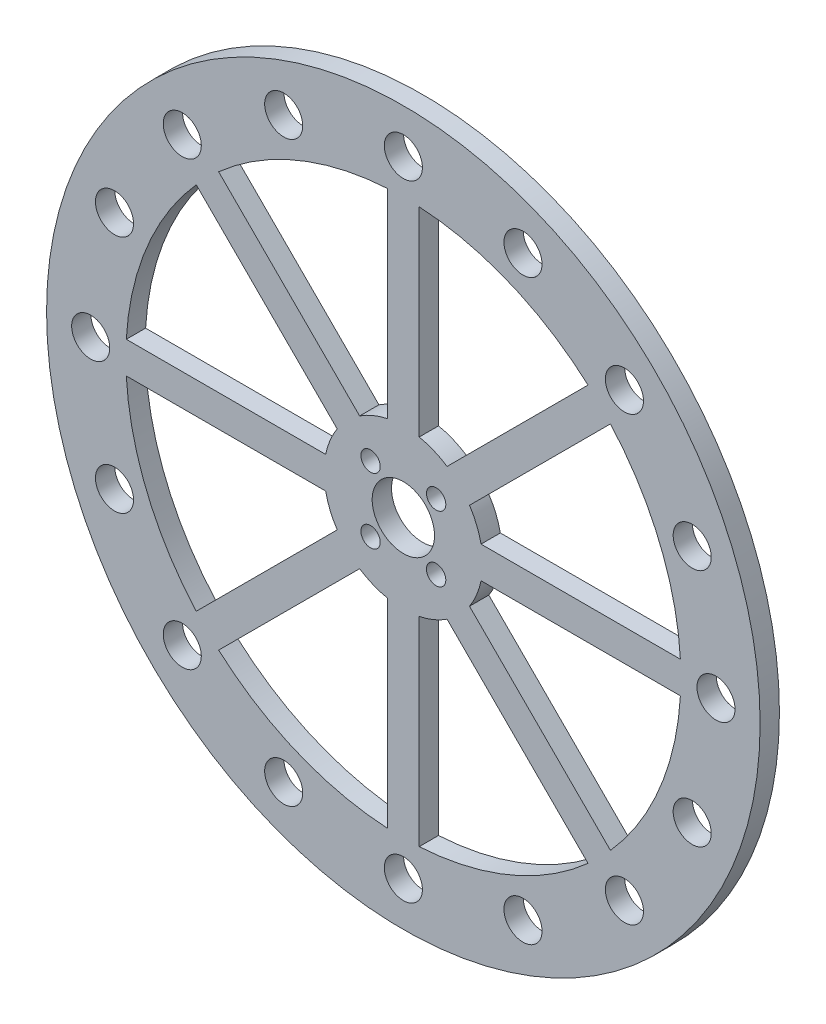
SolidWorks part; units mm, degrees
ref_plane "Front Plane" through (0, 0, 0) normal (0, 0, 1) x (1, 0, 0)
ref_plane "Top Plane" through (0, 0, 0) normal (0, 1, 0) x (1, 0, 0)
ref_plane "Right Plane" through (0, 0, 0) normal (1, 0, 0) x (0, 0, -1)
sketch "Model" plane through (0, 0, 0) normal (0, 0, 1) x (1, 0, 0)
  line L0 (-34.0565, 30.369) -> (-10.8762, 7.1887)
  line L1 (-12.7738, 2.6074) -> (-45.5557, 2.6074)
  line L2 (-7.1887, 10.8762) -> (-30.369, 34.0565)
  line L3 (-2.6074, 45.5557) -> (-2.6074, 12.7738)
  line L4 (2.6074, 12.7738) -> (2.6074, 45.5557)
  line L5 (30.369, 34.0565) -> (7.1887, 10.8762)
  line L6 (10.8762, 7.1887) -> (34.0565, 30.369)
  line L7 (45.5557, 2.6074) -> (12.7738, 2.6074)
  line L8 (12.7738, -2.6074) -> (45.5557, -2.6074)
  line L9 (34.0565, -30.369) -> (10.8762, -7.1887)
  line L10 (7.1887, -10.8762) -> (30.369, -34.0565)
  line L11 (2.6074, -45.5557) -> (2.6074, -12.7738)
  line L12 (-45.5557, -2.6074) -> (-12.7738, -2.6074)
  line L13 (-10.8762, -7.1887) -> (-34.0565, -30.369)
  line L14 (-2.6074, -12.7738) -> (-2.6074, -45.5557)
  line L15 (-30.369, -34.0565) -> (-7.1887, -10.8762)
  circle A0 centre (5.3894, 5.3586) radius 1.5912
  circle A1 centre (0, 0) radius 5.125
  circle A2 centre (-5.3894, 5.3586) radius 1.5912
  circle A3 centre (-5.3894, -5.4202) radius 1.5912
  circle A4 centre (5.3894, -5.4202) radius 1.5912
  circle A5 centre (-51.4095, 0) radius 3.131
  circle A6 centre (-47.4962, 19.6736) radius 3.131
  circle A7 centre (-36.352, 36.352) radius 3.131
  circle A8 centre (-19.6736, 47.4962) radius 3.131
  circle A9 centre (0, 51.4095) radius 3.131
  circle A10 centre (19.6736, 47.4962) radius 3.131
  circle A11 centre (36.352, 36.352) radius 3.131
  circle A12 centre (47.4962, 19.6736) radius 3.131
  circle A13 centre (51.4095, 0) radius 3.131
  circle A14 centre (47.4962, -19.6736) radius 3.131
  circle A15 centre (36.352, -36.352) radius 3.131
  circle A16 centre (19.6736, -47.4962) radius 3.131
  circle A17 centre (0, -51.4095) radius 3.131
  circle A18 centre (-19.6736, -47.4962) radius 3.131
  circle A19 centre (-36.352, -36.352) radius 3.131
  circle A20 centre (-47.4962, -19.6736) radius 3.131
  circle A21 centre (0, 0) radius 58.6675
  arc A22 (-34.0565, 30.369) -> (-45.5557, 2.6074) centre (0, 0) ccw
  arc A23 (-10.8762, 7.1887) -> (-12.7738, 2.6074) centre (0, 0) ccw
  arc A24 (-2.6074, 12.7738) -> (-7.1887, 10.8762) centre (0, 0) ccw
  arc A25 (-2.6074, 45.5557) -> (-30.369, 34.0565) centre (0, 0) ccw
  arc A26 (7.1887, 10.8762) -> (2.6074, 12.7738) centre (0, 0) ccw
  arc A27 (30.369, 34.0565) -> (2.6074, 45.5557) centre (0, 0) ccw
  arc A28 (12.7738, 2.6074) -> (10.8762, 7.1887) centre (0, 0) ccw
  arc A29 (45.5557, 2.6074) -> (34.0565, 30.369) centre (0, 0) ccw
  arc A30 (10.8762, -7.1887) -> (12.7738, -2.6074) centre (0, 0) ccw
  arc A31 (34.0565, -30.369) -> (45.5557, -2.6074) centre (0, 0) ccw
  arc A32 (2.6074, -12.7738) -> (7.1887, -10.8762) centre (0, 0) ccw
  arc A33 (2.6074, -45.5557) -> (30.369, -34.0565) centre (0, 0) ccw
  arc A34 (-45.5557, -2.6074) -> (-34.0565, -30.369) centre (0, 0) ccw
  arc A35 (-12.7738, -2.6074) -> (-10.8762, -7.1887) centre (0, 0) ccw
  arc A36 (-7.1887, -10.8762) -> (-2.6074, -12.7738) centre (0, 0) ccw
  arc A37 (-30.369, -34.0565) -> (-2.6074, -45.5557) centre (0, 0) ccw
  dimension "D4" = 10.25
  dimension "D1" = 7.6
  dimension "D2" = 7.6
  dimension "D3" = 7.6436
extrude "Boss-Extrude1" add sketch "Model" along normal blind 3.175
